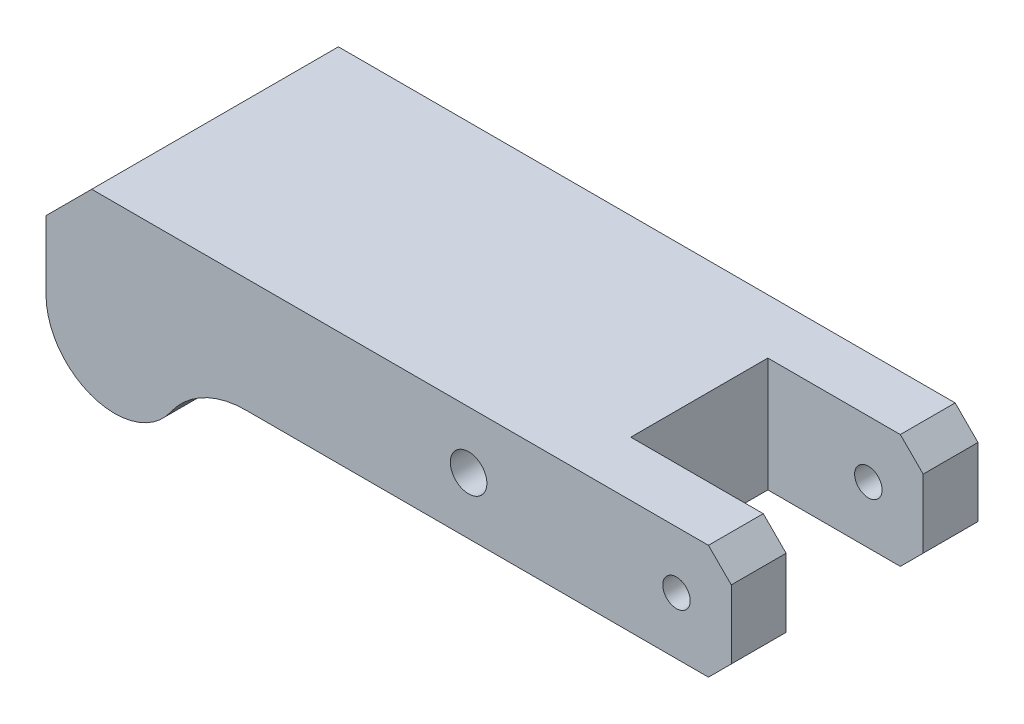
SolidWorks part; units mm, degrees
ref_plane "Front Plane" through (0, 0, 0) normal (0, 0, 1) x (1, 0, 0)
ref_plane "Top Plane" through (0, 0, 0) normal (0, 1, 0) x (1, 0, 0)
ref_plane "Right Plane" through (0, 0, 0) normal (1, 0, 0) x (0, 0, -1)
sketch "Sketch1" plane through (0, 0, 0) normal (0, 0, 1) x (1, 0, 0)
  line L0 (-15, 0) -> (-15, 15)
  line L1 (-15, 15) -> (-5, 25)
  line L2 (-5, 25) -> (130, 25)
  line L3 (135, 20) -> (135, 5)
  line L4 (130, 25) -> (135, 20)
  line L5 (135, 5) -> (130, 0)
  line L6 (130, 0) -> (28.7228, 0)
  arc A0 (-15, 0) -> (12.3098, -8.5714) centre (0, 0) ccw
  arc A1 (28.7228, 0) -> (12.3098, -8.5714) centre (28.7228, -20) ccw
  point P4 (-15, 25)
  point P7 (135, 25)
  point P10 (135, 0)
  dimension "D1" = 30
  dimension "D3" = 40
  dimension "D2" = 150
  dimension "D4" = 10
  dimension "D5" = 45
  dimension "D6" = 5
  dimension "D7" = 25
  dimension "D8" = 5
  dimension "D9" = 45
  dimension "D10" = 20
extrude "Boss-Extrude1" add sketch "Sketch1" against normal blind 54
sketch "Sketch2" plane through (0, 25, 0) normal (0, 1, 0) x (1, 0, 0)
  line L0 (135, 54) -> (135, 0) construction
  line L1 (101, 42) -> (135, 42)
  line L2 (101, 42) -> (101, 12)
  line L3 (101, 12) -> (135, 12)
  line L4 (135, 42) -> (135, 12)
  line L5 (101, 42) -> (135, 12) construction
  line L6 (101, 12) -> (135, 42) construction
  line L7 (130, 0) -> (-5, 0) construction
  line L8 (130, 54) -> (-5, 54) construction
  point P0 (118, 27)
  dimension "D1" = 34
  dimension "D2" = 12
  dimension "D3" = 12
extrude "Cut-Extrude1" cut sketch "Sketch2" against normal blind 54
sketch "Sketch3" plane through (0, 0, 0) normal (0, 0, 1) x (1, 0, 0)
  line L0 (135, 5) -> (135, 20) construction
  line L1 (130, 25) -> (-5, 25) construction
  circle A0 centre (123, 12.5) radius 3
  circle A1 centre (77.5, 12.5) radius 4
  dimension "D1" = 8
  dimension "D2" = 6
  dimension "D3" = 45.5
  dimension "D4" = 12
  dimension "D5" = 12.5
extrude "Cut-Extrude2" cut sketch "Sketch3" against normal blind 54
